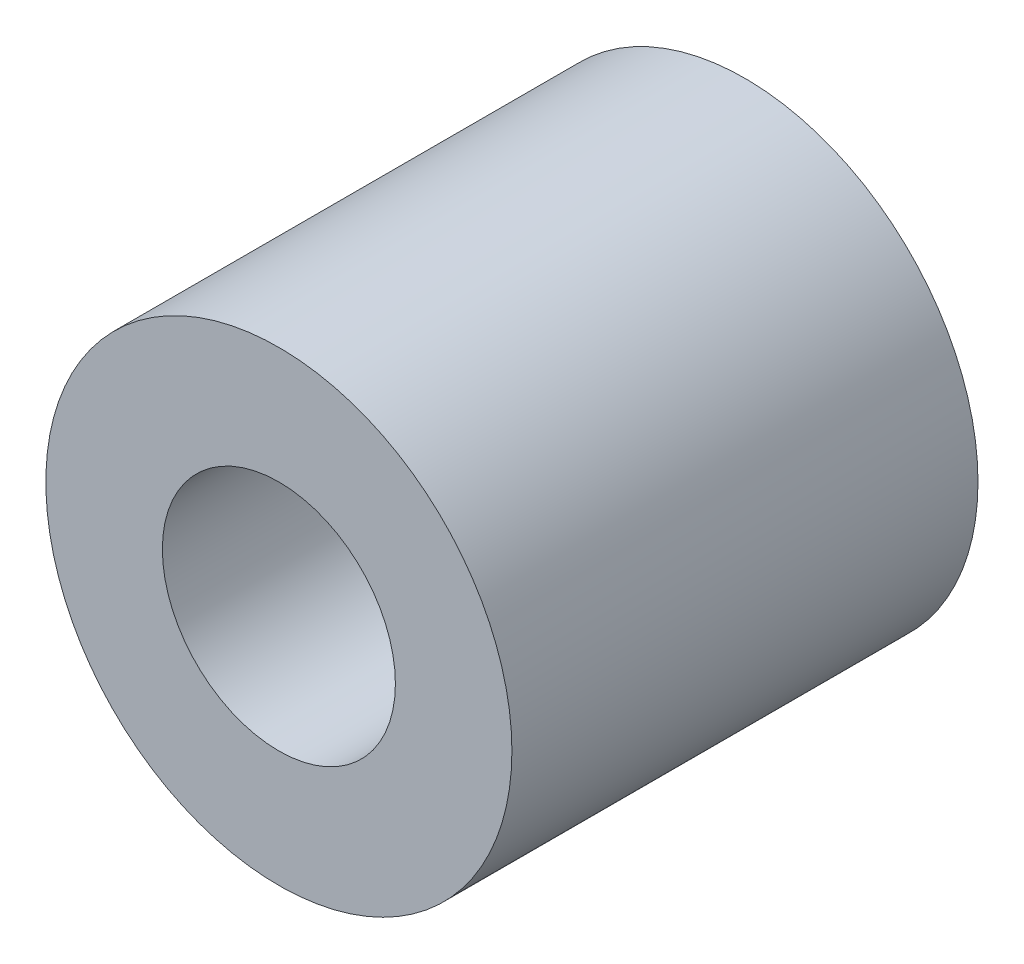
SolidWorks part; units mm, degrees
material "铜"
ref_plane "前视基准面" through (0, 0, 0) normal (0, 0, 1) x (1, 0, 0)
ref_plane "上视基准面" through (0, 0, 0) normal (0, 1, 0) x (1, 0, 0)
ref_plane "右视基准面" through (0, 0, 0) normal (1, 0, 0) x (0, 0, -1)
sketch "草图1" plane through (0, 0, 0) normal (0, 0, 1) x (1, 0, 0)
  circle A0 centre (0, 0) radius 1.5
  circle A1 centre (0, 0) radius 3
  dimension "D1" = 3
  dimension "D2" = 6
extrude "凸台-拉伸1" add sketch "草图1" along normal mid plane 6
